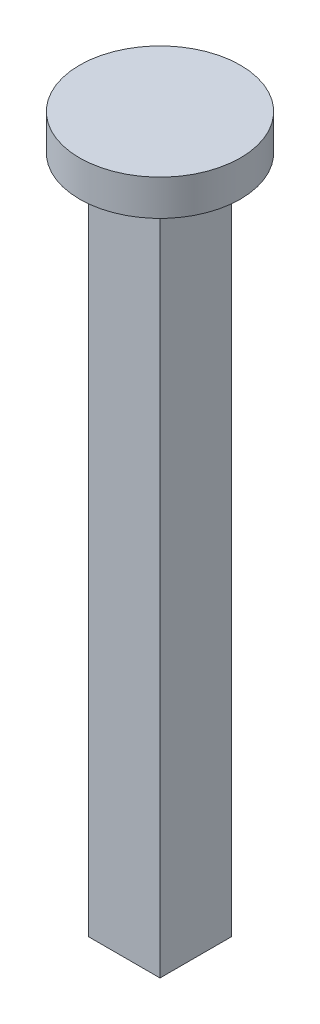
SolidWorks part; units mm, degrees
ref_plane "Front Plane" through (0, 0, 0) normal (0, 0, 1) x (1, 0, 0)
ref_plane "Top Plane" through (0, 0, 0) normal (0, 1, 0) x (1, 0, 0)
ref_plane "Right Plane" through (0, 0, 0) normal (1, 0, 0) x (0, 0, -1)
sketch "Sketch1" plane through (0, 0, 0) normal (0, 0, 1) x (1, 0, 0)
  line L1 (10, -100) -> (-10, -100)
  line L2 (10, -100) -> (10, 100)
  line L3 (10, 100) -> (-10, 100)
  line L4 (-10, -100) -> (-10, 100)
  line L5 (10, -100) -> (-10, 100) construction
  line L6 (10, 100) -> (-10, -100) construction
  point P0 (0, 0)
  dimension "D1" = 200
  dimension "D2" = 20
extrude "Boss-Extrude1" add sketch "Sketch1" along normal blind 20
sketch "Sketch4" plane through (0, 100, 0) normal (0, 1, 0) x (1, 0, 0)
  line L0 (0, 0) -> (0, -20)
  line L2 (10, -20) -> (-10, -20) construction
  circle A0 centre (0, -10) radius 22.5
  point P7 (0, -10)
  dimension "D1" = 45
extrude "Boss-Extrude3" add sketch "Sketch4" against normal blind 10 contours A0
